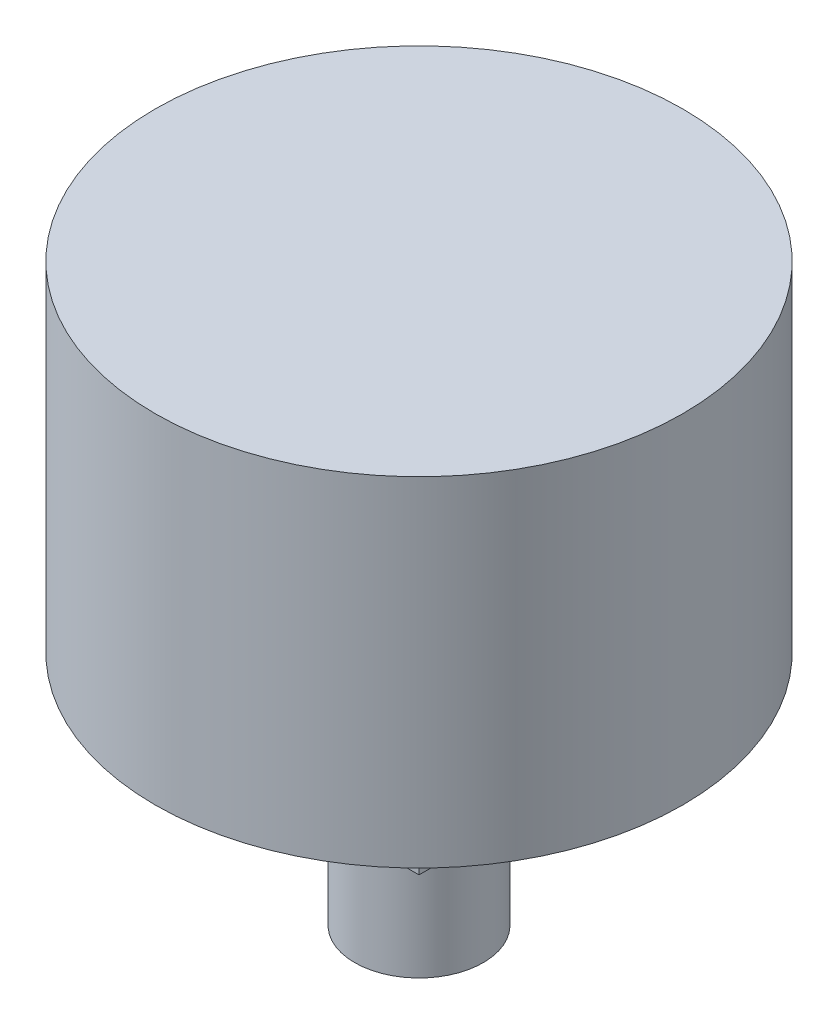
SolidWorks part; units mm, degrees
ref_plane "Front Plane" through (0, 0, 0) normal (0, 0, 1) x (1, 0, 0)
ref_plane "Top Plane" through (0, 0, 0) normal (0, 1, 0) x (1, 0, 0)
ref_plane "Right Plane" through (0, 0, 0) normal (1, 0, 0) x (0, 0, -1)
sketch "Sketch1" plane through (0, 0, 0) normal (0, 1, 0) x (1, 0, 0)
  circle A0 centre (0, 0) radius 20.32
  dimension "D1" = 40.64
extrude "Boss-Extrude1" add sketch "Sketch1" along normal blind 26.0985
sketch "Sketch2" plane through (0, 0, 0) normal (0, -1, 0) x (1, 0, 0)
  line L1 (-7.0231, -7.0231) -> (7.0231, -7.0231)
  line L2 (-7.0231, -7.0231) -> (-7.0231, 7.0231)
  line L3 (-7.0231, 7.0231) -> (7.0231, 7.0231)
  line L4 (7.0231, -7.0231) -> (7.0231, 7.0231)
  line L5 (-7.0231, -7.0231) -> (7.0231, 7.0231) construction
  line L6 (-7.0231, 7.0231) -> (7.0231, -7.0231) construction
  point P0 (0, 0)
  dimension "D1" = 14.0462
extrude "Boss-Extrude2" add sketch "Sketch2" along normal blind 7.7978
sketch "Sketch3" plane through (0, -7.7978, 0) normal (0, -1, 0) x (1, 0, 0)
  circle A0 centre (0, 0) radius 4.953
  dimension "D1" = 9.906
extrude "Boss-Extrude3" add sketch "Sketch3" along normal offset from surface (10.4013 mm away) 18.1991 up to face at (0, 0, 20.32) offset beyond the face yes
